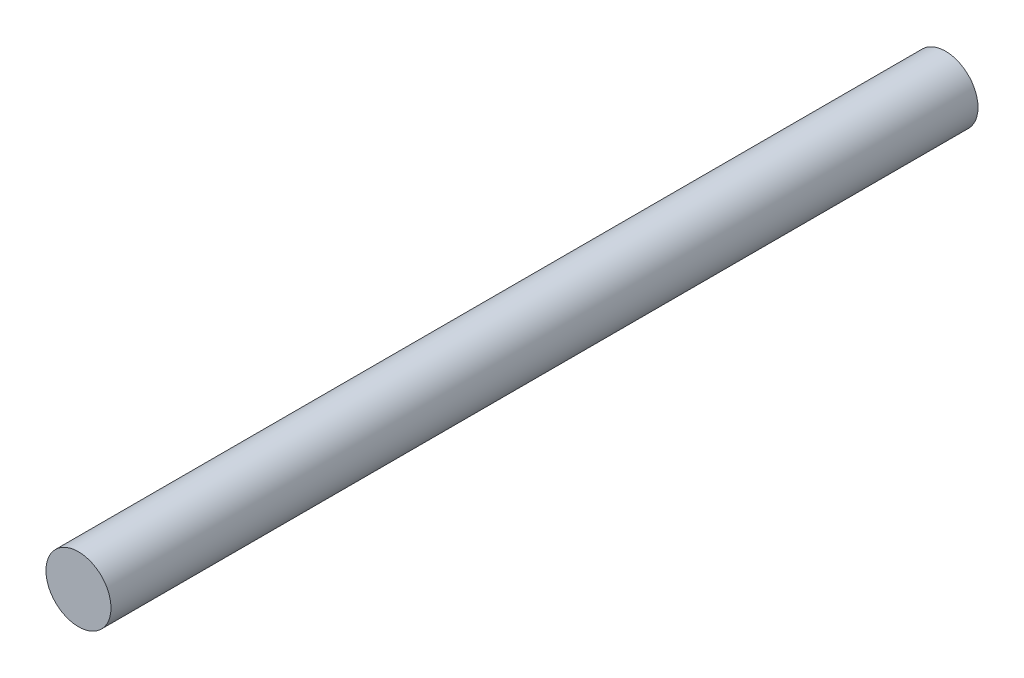
SolidWorks part; units mm, degrees
ref_plane "Front" through (0, 0, 0) normal (0, 0, 1) x (1, 0, 0)
ref_plane "Top" through (0, 0, 0) normal (0, 1, 0) x (1, 0, 0)
ref_plane "Right" through (0, 0, 0) normal (1, 0, 0) x (0, 0, -1)
sketch "Esquisse1" plane through (0, 0, 0) normal (0, 0, 1) x (1, 0, 0)
  circle A0 centre (0, 0) radius 1.5
  dimension "D1" = 3
extrude "Boss.-Extru.1" add sketch "Esquisse1" along normal blind 40
